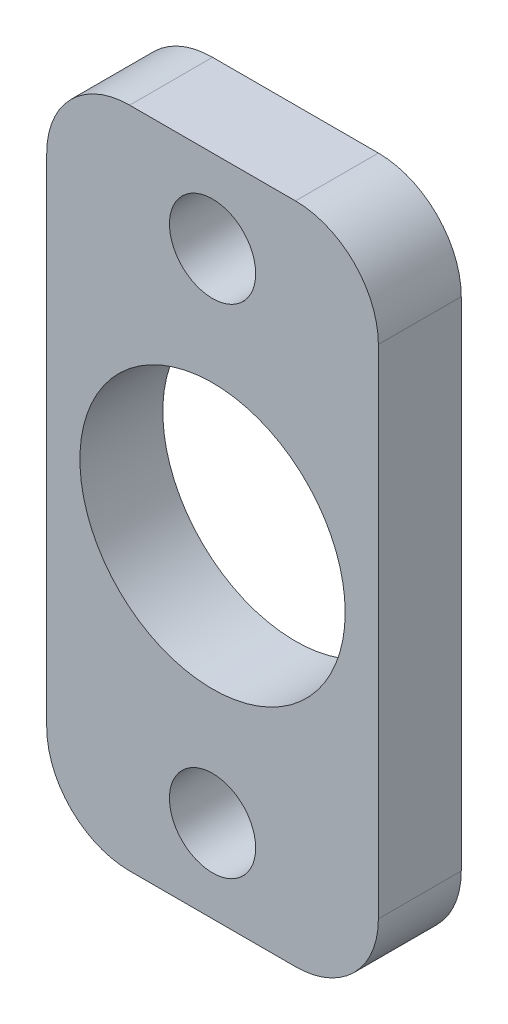
SolidWorks part; units mm, degrees
material "Acrílico (médio-alto impacto)"
ref_plane "Plano frontal" through (0, 0, 0) normal (0, 0, 1) x (1, 0, 0)
ref_plane "Plano superior" through (0, 0, 0) normal (0, 1, 0) x (1, 0, 0)
ref_plane "Plano direito" through (0, 0, 0) normal (1, 0, 0) x (0, 0, -1)
sketch "Esboço1" plane through (0, 0, 0) normal (0, 0, 1) x (1, 0, 0)
  line L1 (-10, 20) -> (10, 20)
  line L2 (-10, 20) -> (-10, -20)
  line L3 (-10, -20) -> (10, -20)
  line L4 (10, 20) -> (10, -20)
  line L5 (-10, 20) -> (10, -20) construction
  line L6 (-10, -20) -> (10, 20) construction
  circle A0 centre (0, 0) radius 8
  point P0 (0, 0)
  dimension "D3" = 16
  dimension "D1" = 20
  dimension "D2" = 40
extrude "Ressalto-extrusão1" add sketch "Esboço1" along normal mid plane 5
sketch "Esboço2" plane through (0, 0, 2.5) normal (0, 0, 1) x (1, 0, 0)
  line L0 (0, -20) -> (0, 20) construction
  line L1 (-10, -20) -> (10, -20) construction
  line L2 (10, 20) -> (-10, 20) construction
  circle A0 centre (0, -15) radius 2.6
  circle A1 centre (0, 0) radius 8 construction
  dimension "D1" = 5.2
  dimension "D2" = 15
extrude "Corte-extrusão1" cut sketch "Esboço2" against normal through all
mirror "Espelhar1" about plane through (0, 0, 0) normal (0, 1, 0) of "Corte-extrusão1"
fillet "Filete1" radius 5 4 edges at (-10, -20, 0) (-10, 20, 0) (10, 20, 0) (10, -20, 0)
